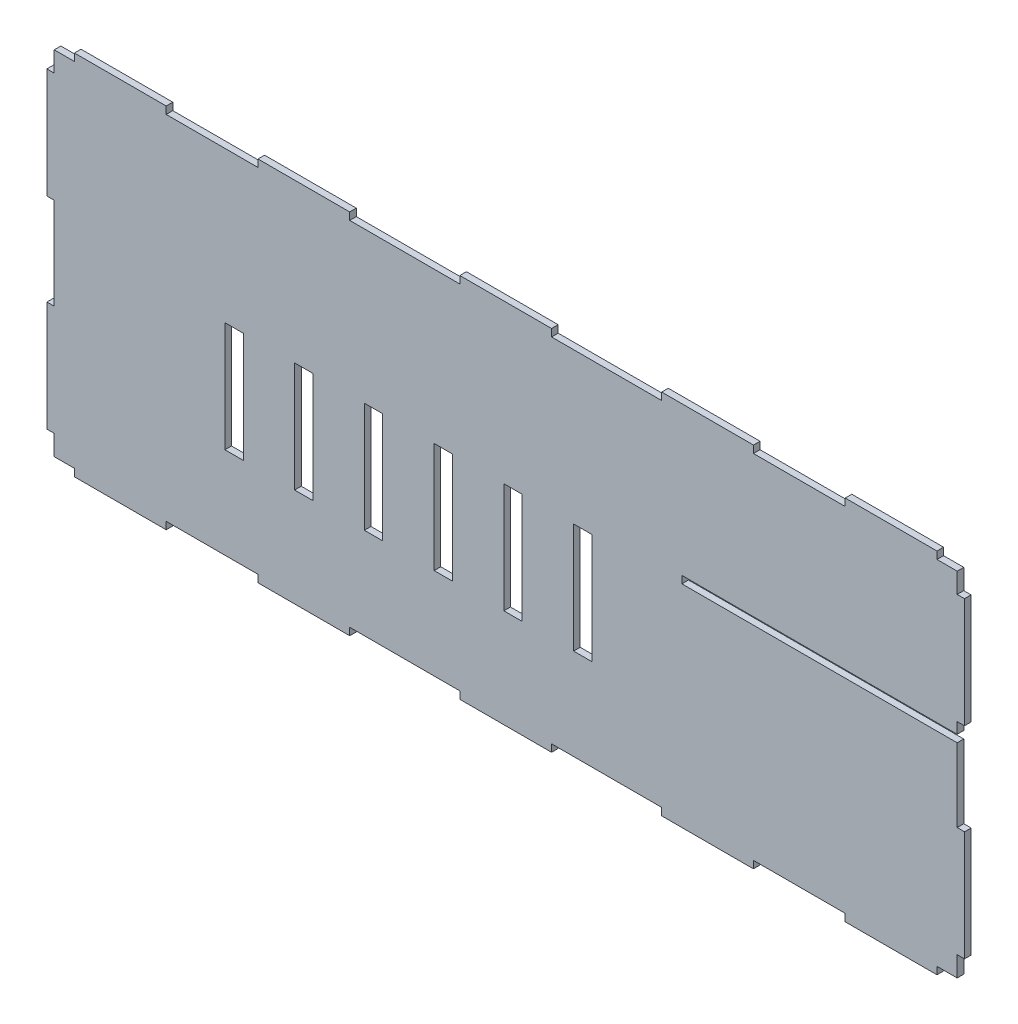
SolidWorks part; units mm, degrees
material "处理板，复杂型"
ref_plane "前视基准面" through (0, 0, 0) normal (0, 0, 1) x (1, 0, 0)
ref_plane "上视基准面" through (0, 0, 0) normal (0, 1, 0) x (1, 0, 0)
ref_plane "右视基准面" through (0, 0, 0) normal (1, 0, 0) x (0, 0, -1)
sketch "草图1" plane through (0, 0, 0) normal (0, 0, 1) x (1, 0, 0)
  line L0 (-342.2535, 0) -> (646.4789, 0) construction
  line L1 (-250, 100) -> (250, 100)
  line L2 (-250, 100) -> (-250, -100)
  line L3 (-250, -100) -> (250, -100)
  line L4 (250, 100) -> (250, -100)
  line L5 (0, 347.1831) -> (0, -385.2113) construction
  dimension "D1" = 200
  dimension "D2" = 500
  dimension "D3" = 250
  dimension "D4" = 100
extrude "凸台-拉伸1" add sketch "草图1" along normal blind 3.6
sketch "草图3" plane through (0, 0, 3.6) normal (0, 0, 1) x (1, 0, 0)
  line L0 (-246, 192.9658) -> (-246, -192.96) construction
  line L1 (246, 192.9658) -> (246, -192.96) construction
  line L2 (250, -100) -> (250, 100) construction
  line L3 (-250, 100) -> (-250, -100) construction
  line L4 (-300.7416, 0) -> (304.897, 0) construction
  line L5 (0, 188.291) -> (0, -192.96) construction
  line L7 (-246, 25) -> (-250, 25)
  line L8 (-246, 25) -> (-246, -25)
  line L9 (-246, -25) -> (-250, -25)
  line L10 (-250, 25) -> (-250, -25)
  line L11 (-246, 135) -> (-250, 135)
  line L12 (-246, 135) -> (-246, 85)
  line L13 (-246, 85) -> (-250, 85)
  line L14 (-250, 135) -> (-250, 85)
  line L15 (-246, -85) -> (-250, -85)
  line L16 (-246, -85) -> (-246, -135)
  line L17 (-246, -135) -> (-250, -135)
  line L18 (-250, -85) -> (-250, -135)
  line L19 (246, 135) -> (250, 135)
  line L20 (246, 135) -> (246, 85)
  line L21 (246, 85) -> (250, 85)
  line L22 (250, 135) -> (250, 85)
  line L23 (246, 25) -> (250, 25)
  line L24 (246, 25) -> (246, -25)
  line L25 (246, -25) -> (250, -25)
  line L26 (250, 25) -> (250, -25)
  line L27 (246, -85) -> (250, -85)
  line L28 (246, -85) -> (246, -135)
  line L29 (246, -135) -> (250, -135)
  line L30 (250, -85) -> (250, -135)
  dimension "D1" = 4
  dimension "D2" = 4
  dimension "D3" = 50
  dimension "D4" = 25
  dimension "D5" = 50
  dimension "D6" = 60
  dimension "D7" = 60
  dimension "D8" = 50
  dimension "D9" = 50
  dimension "D10" = 50
  dimension "D11" = 50
  dimension "D12" = 25
  dimension "D13" = 60
  dimension "D14" = 60
extrude "切除-拉伸2" cut sketch "草图3" against normal blind 3.6
sketch "草图4" plane through (0, 0, 3.6) normal (0, 0, 1) x (1, 0, 0)
  line L0 (-291.9116, -96) -> (-235, -96)
  line L1 (-246, -100) -> (246, -100) construction
  line L2 (0, 145.1767) -> (0, -169.5892) construction
  line L3 (-311.1299, 0) -> (273.2126, 0) construction
  line L4 (-185, -96) -> (-135, -96)
  line L6 (-25, -96) -> (-25, -100)
  line L8 (25, -96) -> (25, -100)
  line L10 (-135, -96) -> (-135, -100)
  line L12 (-85, -96) -> (-85, -100)
  line L14 (-235, -96) -> (-235, -100)
  line L16 (-185, -96) -> (-185, -100)
  line L18 (85, -96) -> (85, -100)
  line L20 (135, -96) -> (135, -100)
  line L22 (185, -96) -> (185, -100)
  line L24 (235, -96) -> (235, -100)
  line L25 (-85, -96) -> (-25, -96)
  line L26 (25, -96) -> (85, -96)
  line L27 (135, -96) -> (185, -96)
  line L28 (235, -96) -> (292.9617, -96)
  line L29 (-291.9116, -96) -> (-291.9116, -100)
  line L30 (-291.9116, -100) -> (-235, -100)
  line L31 (-185, -100) -> (-135, -100)
  line L32 (-85, -100) -> (-25, -100)
  line L33 (25, -100) -> (85, -100)
  line L34 (135, -100) -> (185, -100)
  line L35 (235, -100) -> (292.9617, -100)
  line L36 (292.9617, -100) -> (292.9617, -96)
  line L37 (235, 100) -> (292.9617, 100)
  line L38 (235, 96) -> (235, 100)
  line L39 (235, 96) -> (292.9617, 96)
  line L40 (292.9617, 100) -> (292.9617, 96)
  line L41 (135, 96) -> (135, 100)
  line L42 (135, 96) -> (185, 96)
  line L43 (185, 96) -> (185, 100)
  line L44 (135, 100) -> (185, 100)
  line L45 (25, 96) -> (25, 100)
  line L46 (25, 96) -> (85, 96)
  line L47 (85, 96) -> (85, 100)
  line L48 (25, 100) -> (85, 100)
  line L49 (-85, 96) -> (-85, 100)
  line L50 (-85, 96) -> (-25, 96)
  line L51 (-25, 96) -> (-25, 100)
  line L52 (-85, 100) -> (-25, 100)
  line L53 (-185, 96) -> (-185, 100)
  line L54 (-185, 96) -> (-135, 96)
  line L55 (-135, 96) -> (-135, 100)
  line L56 (-185, 100) -> (-135, 100)
  line L57 (-291.9116, 96) -> (-291.9116, 100)
  line L58 (-291.9116, 96) -> (-235, 96)
  line L59 (-235, 96) -> (-235, 100)
  line L60 (-291.9116, 100) -> (-235, 100)
  dimension "D1" = 4
  dimension "D2" = 50
  dimension "D3" = 25
  dimension "D4" = 50
  dimension "D5" = 50
  dimension "D6" = 50
  dimension "D7" = 50
  dimension "D8" = 60
  dimension "D9" = 50
  dimension "D10" = 60
  dimension "D11" = 50
extrude "切除-拉伸3" cut sketch "草图4" against normal blind 10
sketch "草图5" plane through (0, 0, 3.6) normal (0, 0, 1) x (1, 0, 0)
  line L0 (-153, 121.9859) -> (-153, -237.0431) construction
  line L1 (-258.4798, -16.2374) -> (279.114, -16.2374) construction
  line L2 (-97, -41.4) -> (-97, 8.6) construction
  line L3 (-153, 13.7626) -> (-143, 13.7626)
  line L4 (-153, 13.7626) -> (-153, -46.2374)
  line L5 (-153, -46.2374) -> (-143, -46.2374)
  line L6 (-143, 13.7626) -> (-143, -46.2374)
  line L7 (-115, 13.7626) -> (-105, 13.7626)
  line L8 (-115, 13.7626) -> (-115, -46.2374)
  line L9 (-115, -46.2374) -> (-105, -46.2374)
  line L10 (-105, 13.7626) -> (-105, -46.2374)
  line L11 (-77, 13.7626) -> (-67, 13.7626)
  line L12 (-77, 13.7626) -> (-77, -46.2374)
  line L13 (-77, -46.2374) -> (-67, -46.2374)
  line L14 (-67, 13.7626) -> (-67, -46.2374)
  line L15 (-39, 13.7626) -> (-29, 13.7626)
  line L16 (-39, 13.7626) -> (-39, -46.2374)
  line L17 (-39, -46.2374) -> (-29, -46.2374)
  line L18 (-29, 13.7626) -> (-29, -46.2374)
  line L19 (-1, 13.7626) -> (9, 13.7626)
  line L20 (-1, 13.7626) -> (-1, -46.2374)
  line L21 (-1, -46.2374) -> (9, -46.2374)
  line L22 (9, 13.7626) -> (9, -46.2374)
  line L23 (37, 13.7626) -> (47, 13.7626)
  line L24 (37, 13.7626) -> (37, -46.2374)
  line L25 (37, -46.2374) -> (47, -46.2374)
  line L26 (47, 13.7626) -> (47, -46.2374)
  line L27 (-59, -41.4) -> (-59, 8.6) construction
  line L28 (-21, -41.4) -> (-21, 8.6) construction
  line L29 (17, -41.4) -> (17, 8.6) construction
  dimension "D1" = 10
  dimension "D2" = 60
  dimension "D3" = 30
  dimension "D4" = 10
  dimension "D5" = 10
  dimension "D6" = 10
  dimension "D7" = 10
  dimension "D8" = 10
  dimension "D9" = 60
  dimension "D10" = 60
  dimension "D11" = 60
  dimension "D12" = 60
  dimension "D13" = 60
  dimension "D14" = 0
  dimension "D15" = 0
  dimension "D16" = 0
  dimension "D17" = 0
  dimension "D18" = 0
  dimension "D19" = 20
  dimension "D20" = 20
  dimension "D21" = 20
  dimension "D22" = 20
  dimension "D23" = 20
extrude "切除-拉伸4" cut sketch "草图5" against normal through all
sketch "草图6" plane through (0, 0, 3.6) normal (0, 0, 1) x (1, 0, 0)
  line L0 (96, 15) -> (359.4929, 15)
  line L1 (246, 25) -> (246, -25) construction
  line L2 (96, 15) -> (290.8996, 15)
  line L3 (96, 15) -> (96, 19)
  line L4 (96, 19) -> (290.8996, 19)
  line L5 (290.8996, 15) -> (290.8996, 19)
  dimension "D1" = 15
  dimension "D2" = 4
  dimension "D3" = 150
extrude "切除-拉伸5" cut sketch "草图6" against normal through all contours L0 L5 L4 L3
